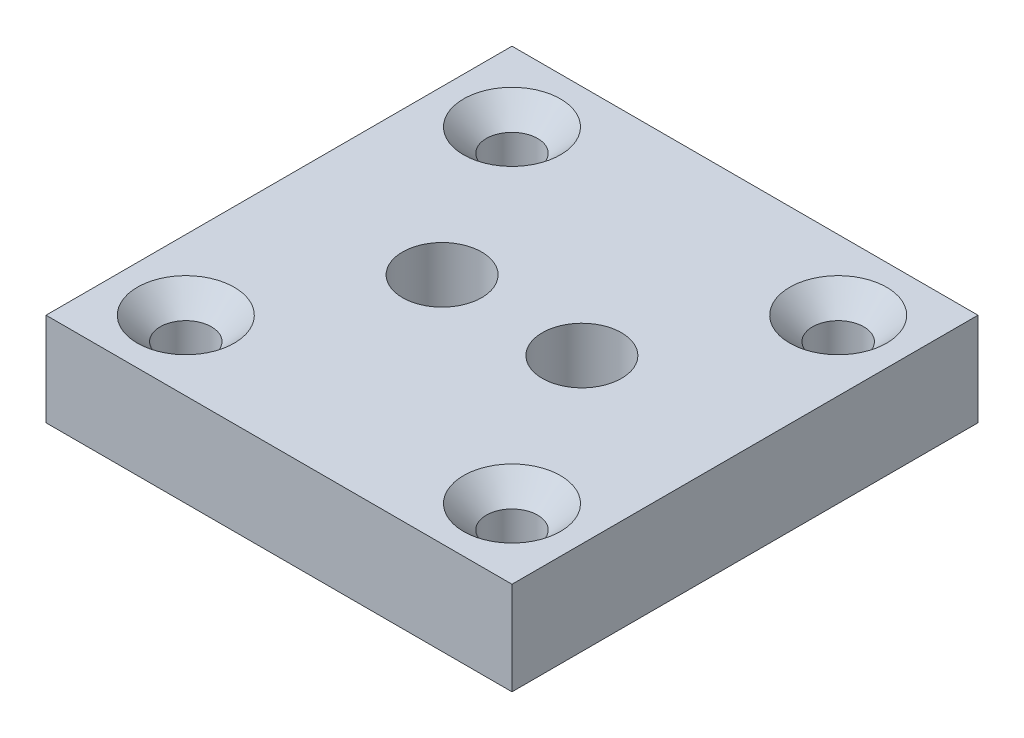
SolidWorks part; units mm, degrees
ref_plane "Front Plane" through (0, 0, 0) normal (0, 0, 1) x (1, 0, 0)
ref_plane "Top Plane" through (0, 0, 0) normal (0, 1, 0) x (1, 0, 0)
ref_plane "Right Plane" through (0, 0, 0) normal (1, 0, 0) x (0, 0, -1)
sketch "Sketch2" plane through (0, 0, 0) normal (0, 0, 1) x (1, 0, 0)
  line L1 (0, 0) -> (50, 0)
  line L2 (0, 0) -> (0, 10)
  line L3 (0, 10) -> (50, 10)
  line L4 (50, 0) -> (50, 10)
  dimension "D1" = 10
  dimension "D2" = 50
extrude "Boss-Extrude1" add sketch "Sketch2" along normal blind 50 contours L2 L1 L4 L3
hole_wizard "Tap Drill for M10 Tap1" positions "Sketch5" profile "Sketch6" hole size "M10" standard "ISO" end condition through all
sketch "Sketch5" plane through (0, 10, 0) normal (0, 1, 0) x (1, 0, 0)
  line L0 (0, 0) -> (50, 0) construction
  line L1 (0, -50) -> (0, 0) construction
  line L2 (50, -50) -> (50, 0) construction
  point P0 (17.5, -25)
  point P2 (32.5, -25)
  dimension "D1" = 25
  dimension "D2" = 17.5
  dimension "D3" = 25
  dimension "D4" = 17.5
sketch "Sketch6" plane through (17.5, 10, 25) normal (1, 0, 0) x (0, 0, 1)
  line L0 (0, 0) -> (0, 10)
  line L1 (0, 10) -> (4.25, 10)
  line L2 (4.25, 10) -> (4.25, 0)
  line L5 (4.25, 0) -> (0, 0)
  line L11 (0, -6.35) -> (0, 107.95) construction
  dimension "Thru Hole Dia." = 8.5
  dimension "Thru Hole Depth" = 10
cosmetic thread "Cosmetic Thread1" parameters "D2"=10
cosmetic thread "Cosmetic Thread2" parameters "D2"=10
hole_wizard "CSK for M5 Flat Head Machine Screw2" positions "Sketch12" profile "Sketch13" countersink size "M5" standard "ANSI Metric" end condition through all
sketch "Sketch12" plane through (0, 10, 0) normal (0, 1, 0) x (1, 0, 0)
  line L1 (-17.1595, -25) -> (70.965, -25) construction
  line L4 (25, 9.649) -> (25, -60.6236) construction
  line L6 (0, -50) -> (50, -50) construction
  line L7 (0, -50) -> (0, 0) construction
  point P0 (7.5, -7.5)
  point P2 (42.5, -7.5)
  point P4 (42.5, -42.5)
  point P6 (7.5, -42.5)
  dimension "D1" = 17.5
  dimension "D2" = 25
  dimension "D3" = 25
  dimension "D4" = 17.5
  dimension "D5" = 17.5
  dimension "D6" = 17.5
  dimension "D7" = 17.5
  dimension "D8" = 17.5
  dimension "D9" = 17.5
  dimension "D10" = 17.5
sketch "Sketch13" plane through (7.5, 10, 7.5) normal (1, 0, 0) x (0, 0, 1)
  line L0 (0, 0) -> (0, 10)
  line L1 (0, 10) -> (2.75, 10)
  line L2 (2.75, 10) -> (2.75, 2.45)
  line L3 (2.75, 2.45) -> (5.2, 0)
  line L5 (5.2, 0) -> (0, 0)
  line L6 (-2.75, 2.45) -> (-5.2, 0) construction
  line L11 (0, -6.35) -> (0, 107.95) construction
  dimension "Thru Hole Dia." = 5.5
  dimension "Thru Hole Depth" = 10
  dimension "Near C'Sink Dia." = 10.4
  dimension "Near C'Sink Angle" = 90
